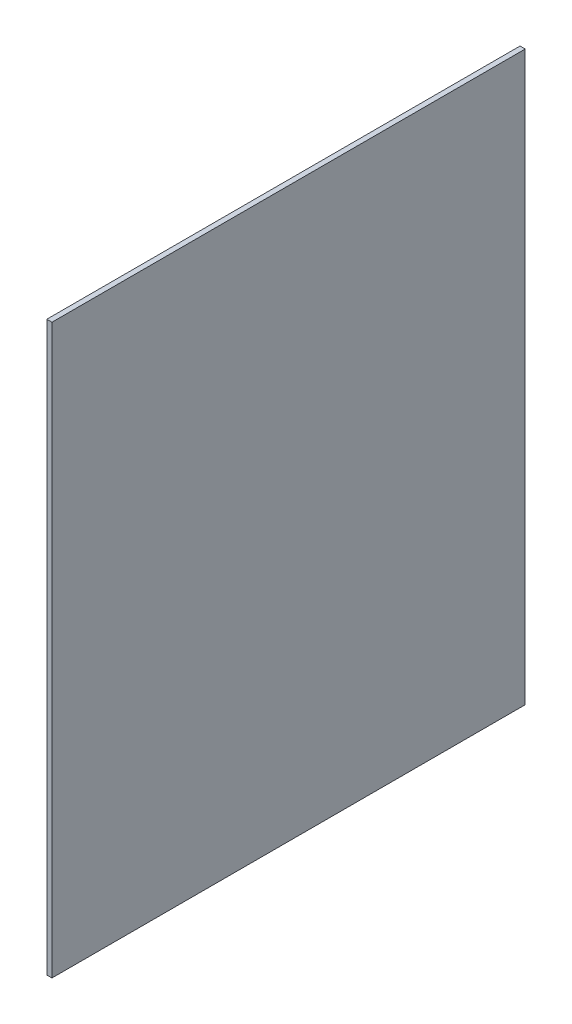
SolidWorks part; units mm, degrees
ref_plane "Płaszczyzna przednia" through (0, 0, 0) normal (0, 0, 1) x (1, 0, 0)
ref_plane "Płaszczyzna górna" through (0, 0, 0) normal (0, 1, 0) x (1, 0, 0)
ref_plane "Płaszczyzna prawa" through (0, 0, 0) normal (1, 0, 0) x (0, 0, -1)
sketch "Szkic3" plane through (0, 0, 0) normal (1, 0, 0) x (0, 0, -1)
  line L1 (0, 0) -> (275, 0)
  line L2 (0, 0) -> (0, 330)
  line L3 (0, 330) -> (275, 330)
  line L4 (275, 0) -> (275, 330)
  dimension "D1" = 275
  dimension "D2" = 330
extrude "Dodanie-wyciągnięcie1" add sketch "Szkic3" along normal blind 3
